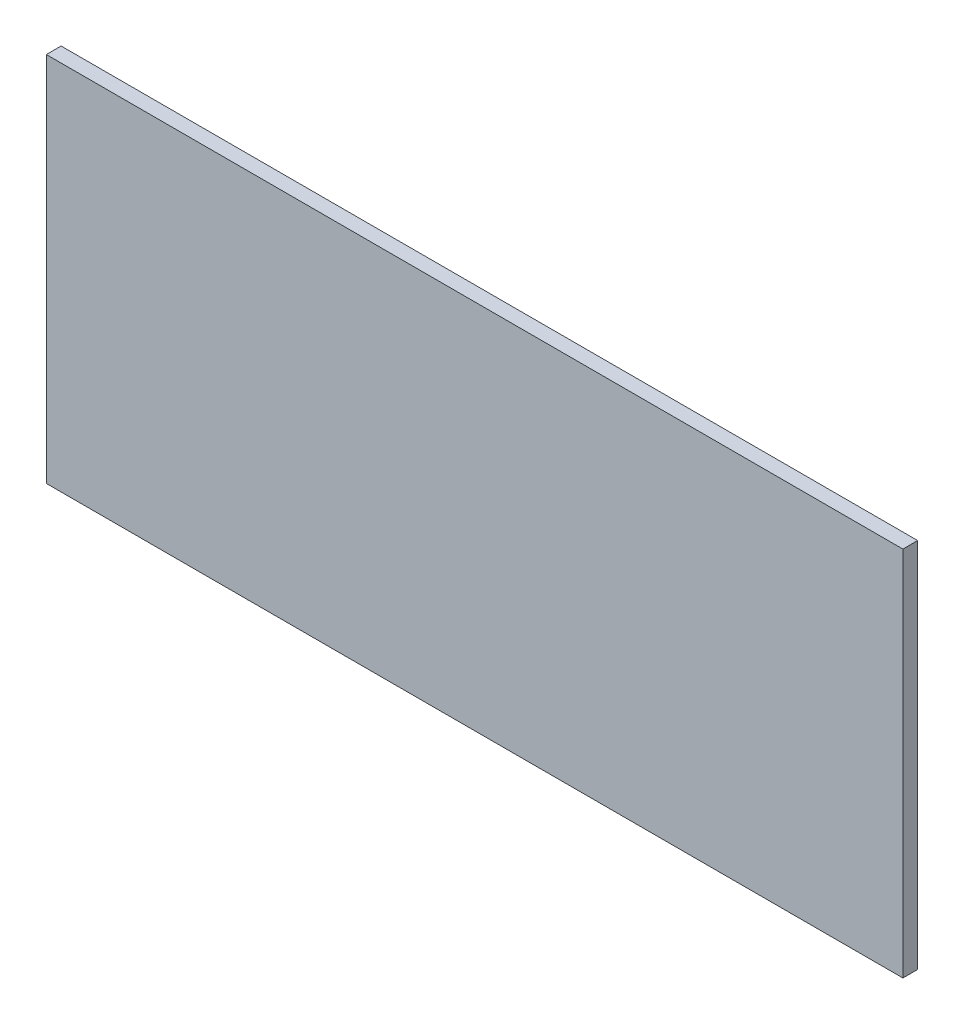
SolidWorks part; units mm, degrees
ref_plane "Plan de face" through (0, 0, 0) normal (0, 0, 1) x (1, 0, 0)
ref_plane "Plan de dessus" through (0, 0, 0) normal (0, 1, 0) x (1, 0, 0)
ref_plane "Plan de droite" through (0, 0, 0) normal (1, 0, 0) x (0, 0, -1)
sketch "Esquisse1" plane through (0, 0, 0) normal (0, 0, 1) x (1, 0, 0)
  line L1 (-208.4671, 50.3304) -> (168.5329, 50.3304)
  line L2 (-208.4671, 50.3304) -> (-208.4671, -113.1696)
  line L3 (-208.4671, -113.1696) -> (168.5329, -113.1696)
  line L4 (168.5329, 50.3304) -> (168.5329, -113.1696)
  dimension "D1" = 377
  dimension "D2" = 163.5
extrude "Boss.-Extru.1" add sketch "Esquisse1" along normal blind 6.5
